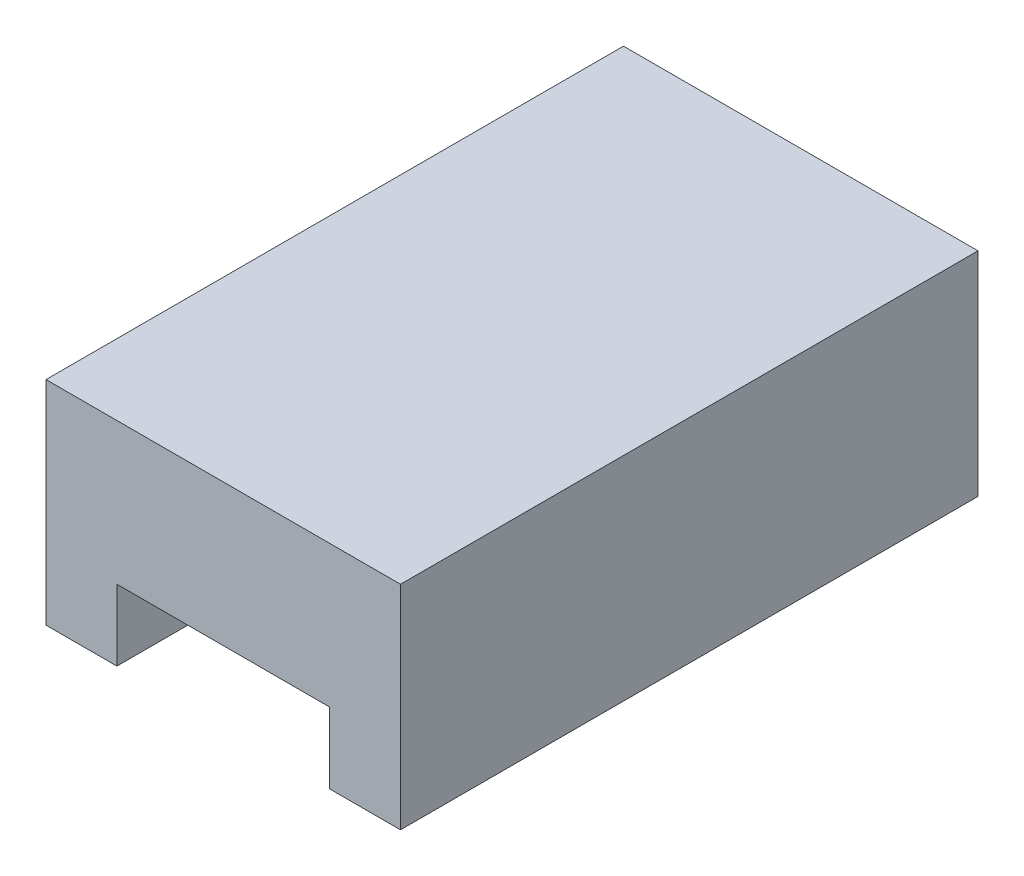
SolidWorks part; units mm, degrees
material "Cedar"
ref_plane "Front Plane" through (0, 0, 0) normal (0, 0, 1) x (1, 0, 0)
ref_plane "Top Plane" through (0, 0, 0) normal (0, 1, 0) x (1, 0, 0)
ref_plane "Right Plane" through (0, 0, 0) normal (1, 0, 0) x (0, 0, -1)
other "Configuration Table"
sketch "Sketch1" plane through (0, 0, 0) normal (0, 0, 1) x (1, 0, 0)
  line L0 (0, 0) -> (101.6, 0)
  line L1 (101.6, 0) -> (101.6, 101.6)
  line L2 (101.6, 101.6) -> (406.4, 101.6)
  line L3 (406.4, 101.6) -> (406.4, 0)
  line L4 (406.4, 0) -> (508, 0)
  line L5 (508, 0) -> (508, 304.8)
  line L6 (508, 304.8) -> (0, 304.8)
  line L7 (0, 304.8) -> (0, 0)
extrude "Extrude1" add sketch "Sketch1" along normal blind 827.532
